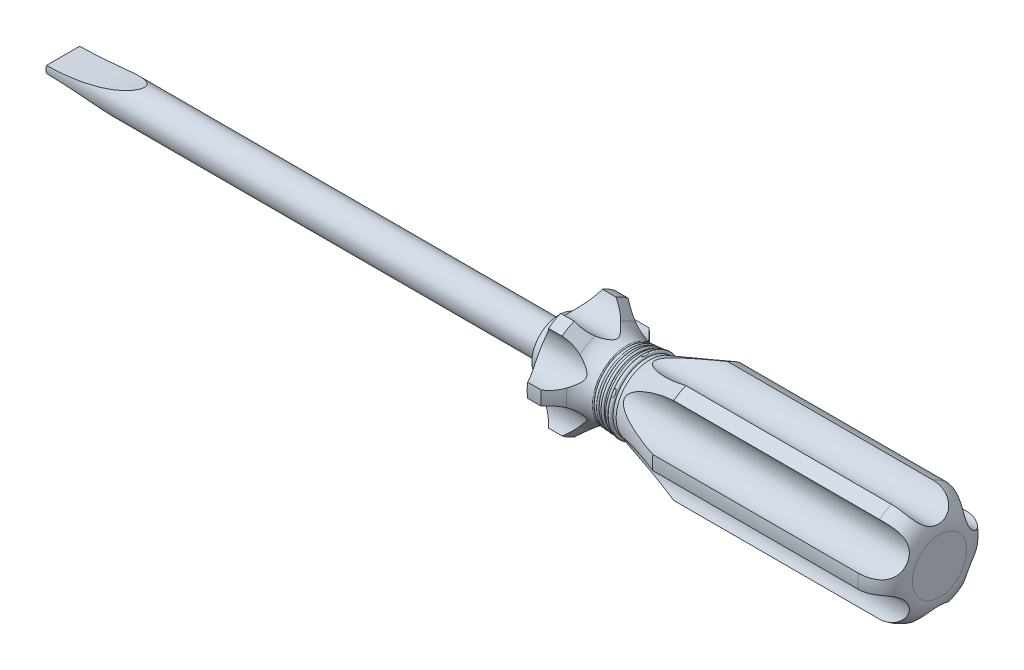
SolidWorks part; units mm, degrees
ref_plane "Front Plane" through (0, 0, 0) normal (0, 0, 1) x (1, 0, 0)
ref_plane "Top Plane" through (0, 0, 0) normal (0, 1, 0) x (1, 0, 0)
ref_plane "Right Plane" through (0, 0, 0) normal (1, 0, 0) x (0, 0, -1)
sketch "Sketch1" plane through (0, 0, 0) normal (0, 1, 0) x (1, 0, 0)
  line L0 (0, 0) -> (0, 4)
  line L1 (0, 0) -> (56, 0) construction
  line L2 (0, 0) -> (0, 8) construction
  line L3 (0, 8) -> (56, 8) construction
  line L4 (56, 0) -> (56, 8) construction
  line L5 (0, 4) -> (1, 4)
  line L6 (1, 4) -> (3.3094, 8)
  line L7 (3.3094, 8) -> (5.3094, 8)
  line L8 (5.3094, 8) -> (7.1867, 6.1227)
  line L9 (10.0152, 4.9511) -> (13.3583, 4.9511)
  line L12 (56, 4) -> (56, 0)
  line L13 (56, 0) -> (0, 0)
  line L14 (13.3583, 4.9511) -> (21.7352, 8)
  line L15 (21.7352, 8) -> (52, 8)
  arc A0 (56, 4) -> (52, 8) centre (52, 4) ccw
  arc A1 (7.1867, 6.1227) -> (10.0152, 4.9511) centre (10.0152, 8.9511) ccw
  point P19 (8.3583, 4.9511)
  dimension "D9" = 4
  dimension "D1" = 56
  dimension "D2" = 8
  dimension "D3" = 120
  dimension "D4" = 135
  dimension "D5" = 20
  dimension "D6" = 1
  dimension "D7" = 2
  dimension "D8" = 5
revolve "Revolve1" add sketch "Sketch1" angle 360 about L13
sketch "Sketch8" plane through (0, 0, 0) normal (0, 0, 1) x (1, 0, 0)
  circle A0 centre (10.0152, 4.9511) radius 0.1
revolve "Revolve8" add sketch "Sketch8" angle 360
sketch "Sketch9" plane through (0, 0, 0) normal (0, 0, 1) x (1, 0, 0)
  line L0 (13.3583, 4.9511) -> (10.1152, 4.9511) construction
  circle A0 centre (10.6982, 4.9511) radius 0.15
  dimension "D1" = 0.3
revolve "Revolve9" add sketch "Sketch9" angle 360
sketch "Sketch11" plane through (0, 0, 0) normal (0, 0, 1) x (1, 0, 0)
  line L2 (13.3583, 4.9511) -> (10.8482, 4.9511) construction
  circle A2 centre (15.9048, 4.9511) radius 0.2
  circle A3 centre (11.4191, 4.9511) radius 0.2
revolve "Revolve13" add sketch "Sketch11" angle 360
sketch "Sketch13" plane through (0, 0, 0) normal (0, 0, 1) x (1, 0, 0)
  circle A0 centre (12.14, 5.0063) radius 0.2
revolve "Revolve14" add sketch "Sketch13" angle 360
sketch "Sketch14" plane through (0, 0, 0) normal (0, 0, 1) x (1, 0, 0)
  circle A0 centre (12.6206, 5.0063) radius 0.2888
revolve "Revolve15" add sketch "Sketch14" angle 360
sketch "Sketch15" plane through (0, 0, 0) normal (-1, 0, 0) x (0, 0, 1)
  line L0 (0, 0) -> (0, 12.5) construction
  circle A1 centre (0, 8.499) radius 3.2716
  dimension "D1" = 12.5
extrude "Cut-Extrude4" cut sketch "Sketch15" against normal through all
pattern_circular "CirPattern1" count 6 over 360 about axis through (0, 0, 0) along (1, 0, 0) of "Cut-Extrude4"
sketch "Sketch17" plane through (0, 0, 0) normal (0, 0, 1) x (1, 0, 0)
  line L3 (0, 4) -> (0, -4) construction
  line L5 (0, 1.5) -> (0, 0)
  line L12 (-54.9441, 0) -> (-54.8794, 0) construction
  line L13 (-54.8794, 0) -> (-39.2068, 0) construction
sketch "Sketch22" plane through (0, 0, 0) normal (-1, 0, 0) x (0, 0, 1)
  circle A0 centre (0, 0) radius 0.8833
sketch "Sketch23" plane through (0, 0, 0) normal (-1, 0, 0) x (0, 0, 1)
  circle A0 centre (0, 0) radius 2.5
  dimension "D1" = 5
extrude "Boss-Extrude7" add sketch "Sketch23" along normal blind 73
sketch "Sketch31" plane through (0, 0, 0) normal (0, 0, 1) x (1, 0, 0)
  line L4 (-73.1478, 0) -> (-33.1914, 0) construction
  line L6 (-73, 0) -> (0, 0) construction
  line L7 (-73, 0.5) -> (-73, 2.5)
  line L8 (-73, 2.5) -> (-73, -2.5) construction
  line L9 (-73, 2.5) -> (-61, 2.5)
  line L10 (0, 2.5) -> (-73, 2.5) construction
  line L14 (-73, -2.5) -> (-61, -2.5)
  line L15 (-73, -0.5) -> (-73, -2.5)
  arc A5 (-61, 2.5) -> (-73, 0.5) centre (-73.6649, 41.4894) cw
  arc A7 (-61, -2.5) -> (-73, -0.5) centre (-73.6649, -41.4894) ccw
  dimension "D2" = 2
  dimension "D1" = 12
extrude "Cut-Extrude8" cut sketch "Sketch31" against normal mid plane 73
